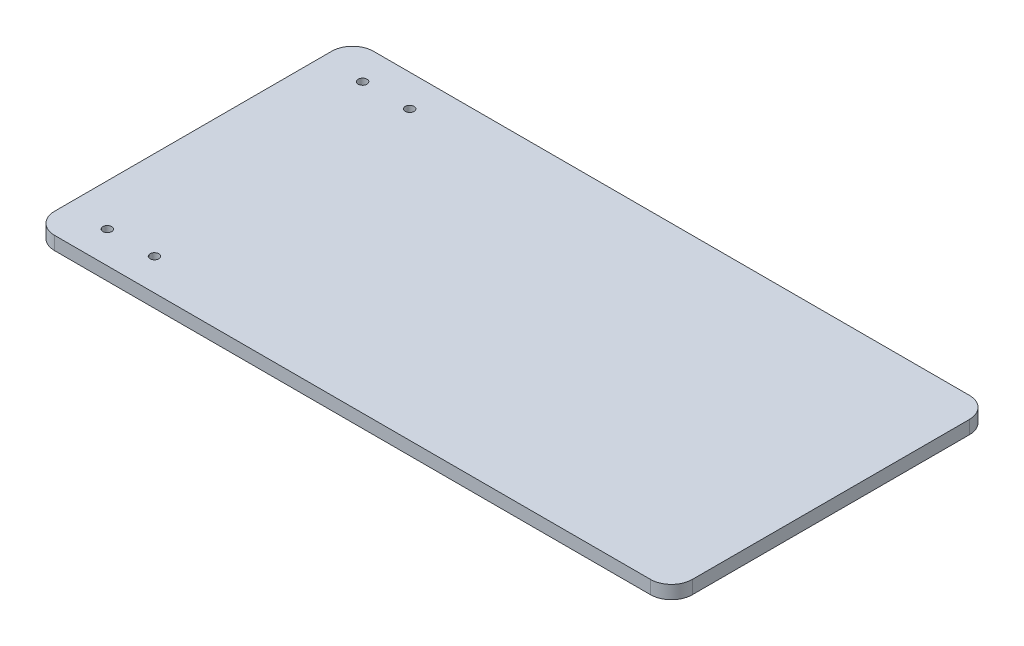
SolidWorks part; units mm, degrees
material "Low Carbon Steel"
ref_plane "Front Plane" through (0, 0, 0) normal (0, 0, 1) x (1, 0, 0)
ref_plane "Top Plane" through (0, 0, 0) normal (0, 1, 0) x (1, 0, 0)
ref_plane "Right Plane" through (0, 0, 0) normal (1, 0, 0) x (0, 0, -1)
sketch "Sketch1" plane through (0, 0, 0) normal (0, 1, 0) x (1, 0, 0)
  line L0 (-152.4, -76.2) -> (152.4, 76.2) construction
  line L1 (-152.4, 76.2) -> (152.4, 76.2)
  line L2 (-152.4, 76.2) -> (-152.4, -76.2)
  line L3 (-152.4, -76.2) -> (152.4, -76.2)
  line L4 (152.4, 76.2) -> (152.4, -76.2)
  dimension "D1" = 152.4
  dimension "D2" = 304.8
extrude "Boss-Extrude1" add sketch "Sketch1" along normal blind 6.35
fillet "Fillet1" radius 10 4 edges at (-152.4, 3.175, -76.2) (152.4, 3.175, -76.2) (152.4, 3.175, 76.2) (-152.4, 3.175, 76.2)
hole_wizard "M5 Tapped Hole1" positions "Sketch3" profile "Sketch2" tap size "M5" standard "Peddi DIN" end condition through all
sketch "Sketch3" plane through (0, 6.35, 0) normal (0, 1, 0) x (1, 0, 0)
  line L0 (-132.4, 61) -> (-132.4, -61) construction
  line L1 (-132.4, -61) -> (-109.9, -61) construction
  line L2 (-109.9, -61) -> (-109.9, 61) construction
  line L5 (0, 0) -> (-109.9, 0) construction
  line L7 (-152.4, 66.2) -> (-152.4, -66.2) construction
  point P0 (-132.4, -61)
  point P2 (-132.4, 61)
  point P4 (-109.9, 61)
  point P6 (-109.9, -61)
  dimension "D1" = 22.5
  dimension "D2" = 122
  dimension "D3" = 20
sketch "Sketch2" plane through (-132.4, 6.35, 61) normal (1, 0, 0) x (0, 0, 1)
  line L0 (0, 0) -> (0, 6.35)
  line L1 (0, 6.35) -> (2.1, 6.35)
  line L2 (2.1, 6.35) -> (2.1, 0)
  line L5 (2.1, 0) -> (0, 0)
  line L11 (0, -6.35) -> (0, 107.95) construction
  dimension "Thru Tap Drill Dia." = 4.2
  dimension "Thru Tap Drill Depth" = 6.35
cosmetic thread "Hole Thread1" parameters "D2"=5
cosmetic thread "Hole Thread2" parameters "D2"=5
cosmetic thread "Hole Thread3" parameters "D2"=5
cosmetic thread "Hole Thread4" parameters "D2"=5
other "Freeze***"
